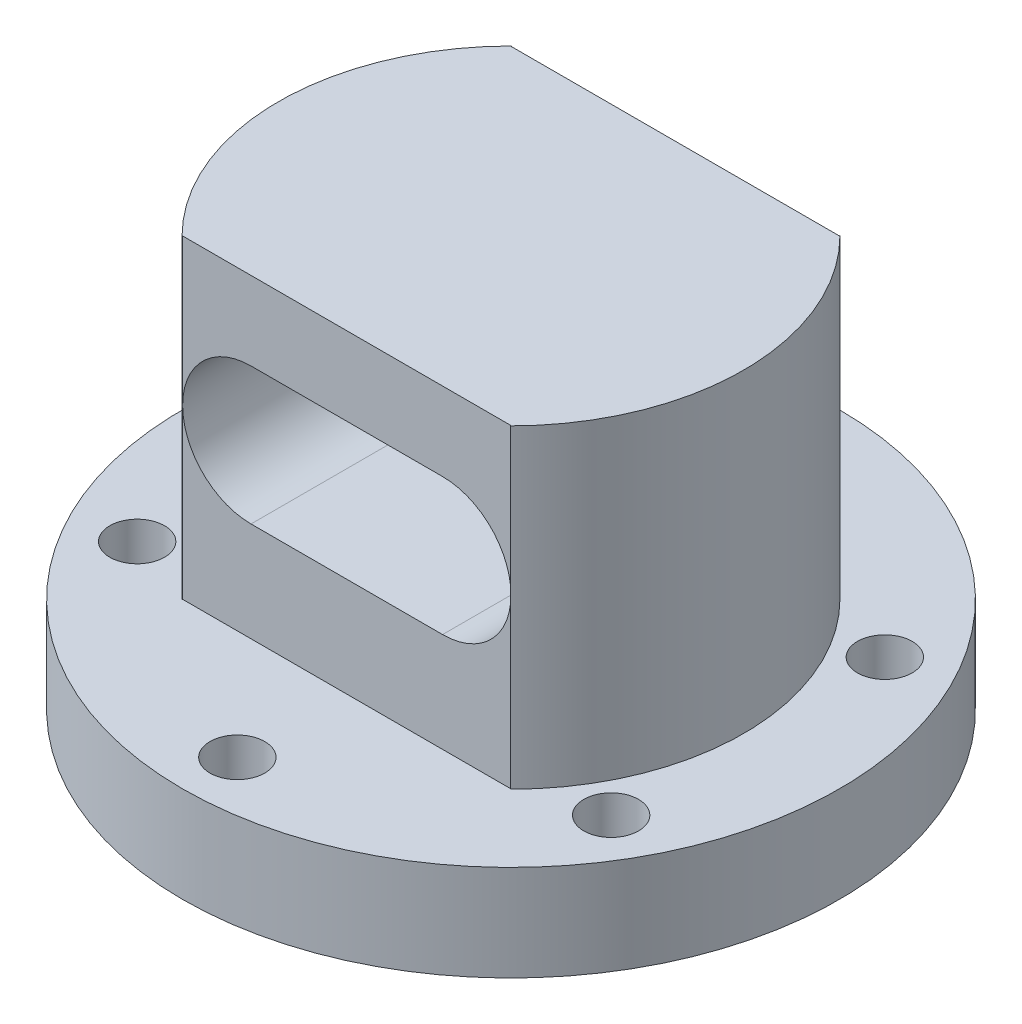
SolidWorks part; units mm, degrees
ref_plane "Спереди" through (0, 0, 0) normal (0, 0, 1) x (1, 0, 0)
ref_plane "Сверху" through (0, 0, 0) normal (0, 1, 0) x (1, 0, 0)
ref_plane "Справа" through (0, 0, 0) normal (1, 0, 0) x (0, 0, -1)
sketch "Эскиз1" plane through (0, 0, 0) normal (0, 1, 0) x (1, 0, 0)
  circle A0 centre (0, 0) radius 24
extrude "Вытянуть1" add sketch "Эскиз1" along normal blind 7
sketch "Эскиз2" plane through (0, 7, 0) normal (0, 1, 0) x (1, 0, 0)
  circle A0 centre (0, 0) radius 17
extrude "Вытянуть2" add sketch "Эскиз2" along normal blind 23
sketch "Эскиз3" plane through (0, 0, 0) normal (0, 0, 1) x (1, 0, 0)
  line L0 (1.0909, 19.2697) -> (-20.5643, 19.2697) construction
  line L1 (-7, 24.2697) -> (7, 24.2697)
  line L2 (-7, 14.2697) -> (7, 14.2697)
  arc A0 (-7, 24.2697) -> (-7, 14.2697) centre (-7, 19.2697) ccw
  arc A1 (7, 14.2697) -> (7, 24.2697) centre (7, 19.2697) ccw
extrude "Вырез-Вытянуть1" cut sketch "Эскиз3" against normal mid plane 46
sketch "Эскиз4" plane through (0, 30, 0) normal (0, 1, 0) x (-1, 0, 0)
  line L0 (12, -12) -> (-12, -12)
  line L1 (-12, -12) -> (-12, -20.0315)
  line L2 (-12, -20.0315) -> (12, -20.0315)
  line L3 (12, -20.0315) -> (12, -12)
  line L4 (15, 0) -> (41.2956, 0) construction
  line L5 (-12, 12) -> (-12, 20.0315)
  line L6 (12, 12) -> (-12, 12)
  line L7 (12, 20.0315) -> (12, 12)
  line L8 (-12, 20.0315) -> (12, 20.0315)
  dimension "D1" = 12
  dimension "D2" = 12
extrude "Вытянуть3" cut sketch "Эскиз4" against normal up to surface (23 mm away) up to face at (0, 7, 24)
sketch "Эскиз5" plane through (0, 7, 0) normal (0, 1, 0) x (1, 0, 0)
  circle A0 centre (0, 20) radius 2
  circle A1 centre (17.3205, 10) radius 2
  circle A2 centre (17.3205, -10) radius 2
  circle A3 centre (0, -20) radius 2
  circle A4 centre (-17.3205, -10) radius 2
  circle A5 centre (-17.3205, 10) radius 2
extrude "Вырез-Вытянуть2" cut sketch "Эскиз5" against normal through all
